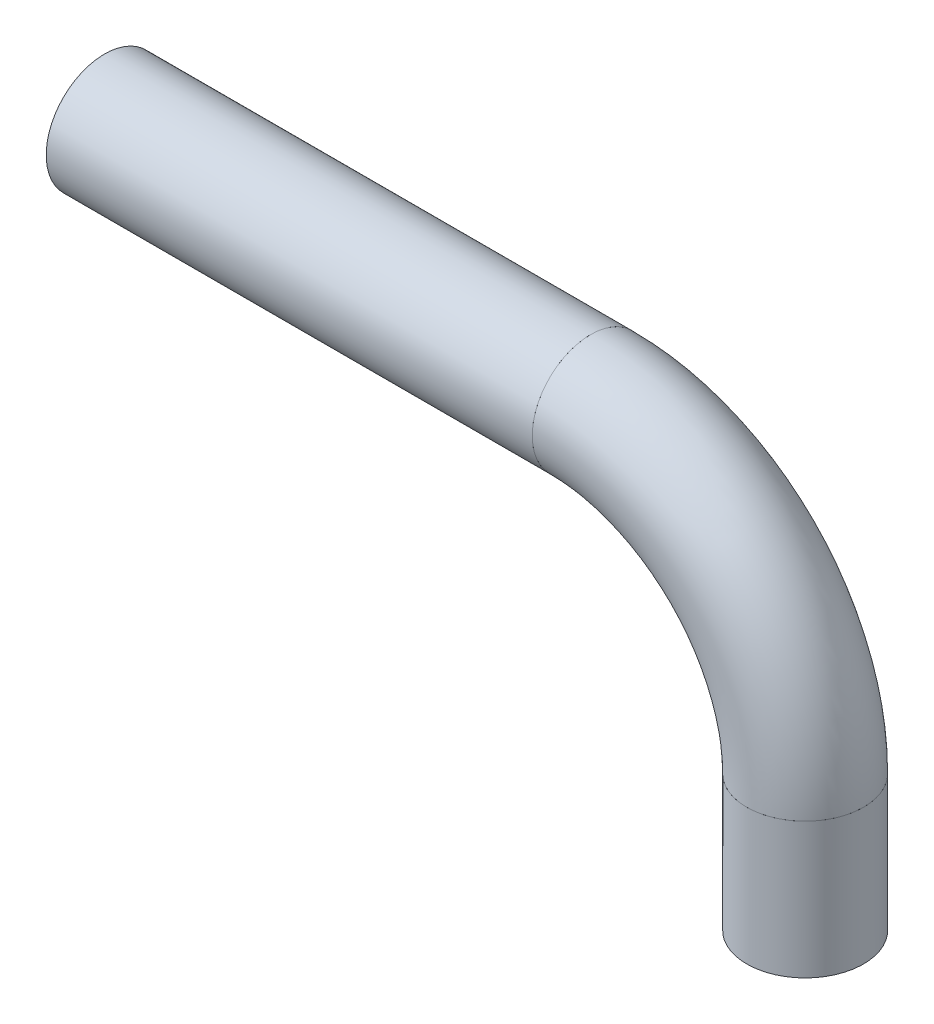
SolidWorks part; units mm, degrees
material "1060 Alloy"
ref_plane "Front Plane" through (0, 0, 0) normal (0, 0, 1) x (1, 0, 0)
ref_plane "Top Plane" through (0, 0, 0) normal (0, 1, 0) x (1, 0, 0)
ref_plane "Right Plane" through (0, 0, 0) normal (1, 0, 0) x (0, 0, -1)
sketch "Sketch1" plane through (0, 0, 0) normal (0, 0, 1) x (1, 0, 0)
  line L0 (0, 0) -> (634.4, 0)
  line L1 (914.4, -280) -> (914.4, -457.2)
  arc A0 (914.4, -280) -> (634.4, 0) centre (634.4, -280) ccw
  point P6 (914.4, 0)
  dimension "D3" = 280
  dimension "D1" = 914.4
  dimension "D2" = 457.2
other "Al round tubing AL RND TUBE 6 OD X 0.5 WALL(1)"
ref_plane "Plane2" through (0, 0, 0) normal (1, 0, 0) x (0, 1, 0)
sketch "Sketch14" plane through (0, 0, 0) normal (1, 0, 0) x (0, 1, 0)
  circle A0 centre (0, 0) radius 63.5
  circle A1 centre (0, 0) radius 76.2
  point P3 (0, 0)
  dimension "In_dia" = 127
  dimension "Out_dia" = 152.4
